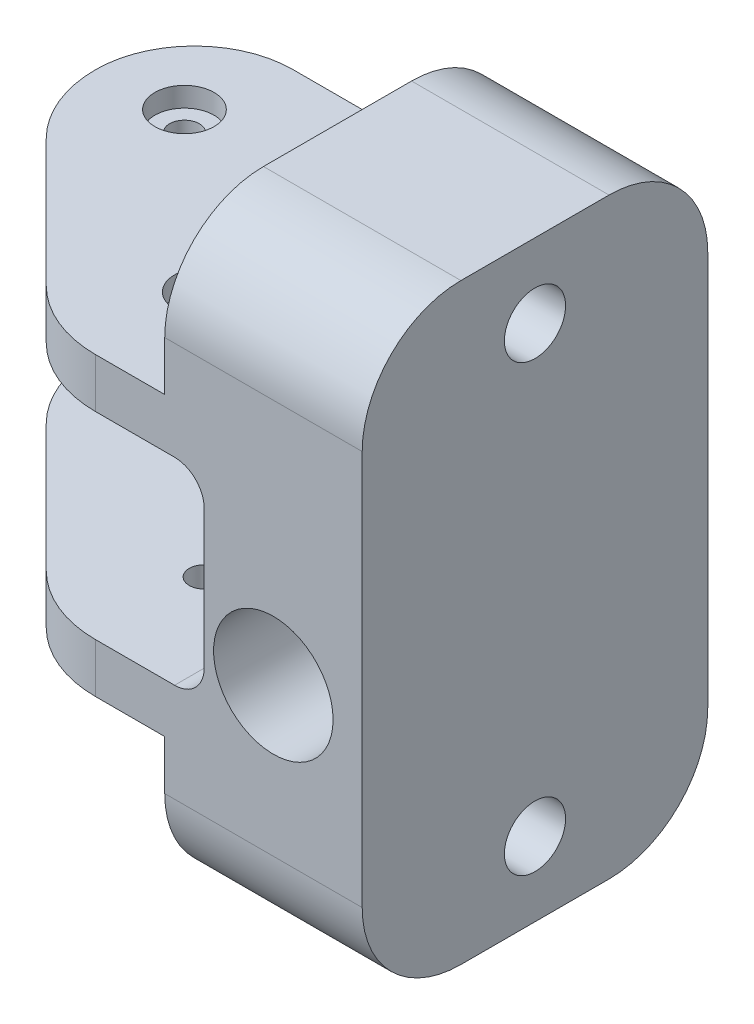
SolidWorks part; units mm, degrees
ref_plane "前视基准面" through (0, 0, 0) normal (0, 0, 1) x (1, 0, 0)
ref_plane "上视基准面" through (0, 0, 0) normal (0, 1, 0) x (1, 0, 0)
ref_plane "右视基准面" through (0, 0, 0) normal (1, 0, 0) x (0, 0, -1)
other "Configuration Table"
sketch "草图1" plane through (0, 0, 0) normal (0, 1, 0) x (1, 0, 0)
  line L0 (-25, -17.5) -> (5, -17.5)
  line L1 (25, 17.5) -> (25, 2.5)
  line L2 (25, 2.5) -> (5, -17.5)
  line L7 (-25, -17.5) -> (-25, 17.5)
  line L8 (-25, 17.5) -> (25, 17.5)
extrude "凸台-拉伸1" add sketch "草图1" along normal blind 60 contours L2 L0 L7 L8 L1
sketch "草图2" plane through (0, 0, -17.5) normal (0, 0, -1) x (-1, 0, 0)
  line L0 (25, 0) -> (7, 0)
  line L1 (25, 0) -> (-25, 0) construction
  line L2 (7, 0) -> (7, 60)
  line L3 (25, 60) -> (-25, 60) construction
  line L5 (-25, 60) -> (7, 60)
  line L6 (-25, 60) -> (-25, 45)
  line L7 (-25, 45) -> (7, 45)
  line L8 (7, 60) -> (7, 45)
  line L9 (-25, 0) -> (7, 0)
  line L10 (-25, 0) -> (-25, 15)
  line L11 (-25, 15) -> (7, 15)
  line L12 (7, 0) -> (7, 15)
  line M11 (-25, 0) -> (25, 0)
  line M13 (25, 60) -> (-25, 60)
  line M14 (-25, 60) -> (-25, 0)
extrude "切除-拉伸1" cut sketch "草图2" against normal blind 60 contours L7 L2 M14 M13 | L11 L2 M14 M11
sketch "草图3" plane through (-25, 0, 0) normal (-1, 0, 0) x (0, 0, 1)
  line L0 (-17.5, 60) -> (17.5, 0)
  line L1 (0, 30) -> (0, 52.5)
  line L2 (0, 30) -> (0, 7.5)
  circle A0 centre (0, 52.5) radius 3
  circle A1 centre (0, 7.5) radius 3
extrude "切除-拉伸2" cut sketch "草图3" against normal blind 30
sketch "草图4" plane through (-25, 0, 0) normal (-1, 0, 0) x (0, 0, 1)
  line L1 (-17.5, 60) -> (-7.5, 60)
  line L2 (-17.5, 60) -> (-17.5, 50)
  line L5 (17.5, 60) -> (7.5, 60)
  line L6 (17.5, 60) -> (17.5, 50)
  line L9 (-17.5, 0) -> (-7.5, 0)
  line L10 (-17.5, 0) -> (-17.5, 10)
  line L13 (17.5, 0) -> (7.5, 0)
  line L14 (17.5, 0) -> (17.5, 10)
  arc A0 (-17.5, 50) -> (-7.5, 60) centre (-7.5, 50) cw
  arc A1 (17.5, 50) -> (7.5, 60) centre (7.5, 50) ccw
  arc A2 (-17.5, 10) -> (-7.5, 0) centre (-7.5, 10) ccw
  arc A3 (17.5, 10) -> (7.5, 0) centre (7.5, 10) cw
  line M20 (-17.5, 0) -> (17.5, 0)
  line M21 (17.5, 0) -> (17.5, 60)
  line M22 (17.5, 60) -> (-17.5, 60)
  line M23 (-17.5, 60) -> (-17.5, 0)
extrude "切除-拉伸3" cut sketch "草图4" against normal blind 30 contours A0 M23 M22 | A1 M21 M22 | A3 M21 M20 | A2 M23 M20
sketch "草图5" plane through (0, 0, -17.5) normal (0, 0, -1) x (-1, 0, 0)
  line L0 (5, 37) -> (5, 23)
  line L2 (11, 37) -> (11, 23)
  arc A0 (11, 23) -> (5, 23) centre (8, 23) cw
  arc A1 (5, 37) -> (11, 37) centre (8, 37) cw
extrude "切除-拉伸4" cut sketch "草图5" against normal blind 50
sketch "草图6" plane through (0, 0, -17.5) normal (0, 0, -1) x (-1, 0, 0)
  circle A1 centre (18, 25) radius 5
extrude "切除-拉伸5" cut sketch "草图6" against normal blind 50
sketch "草图7" plane through (0, 0, -17.5) normal (0, 0, -1) x (-1, 0, 0)
  line L0 (-8, 40) -> (-25, 40)
  line L1 (-25, 45) -> (-25, 15) construction
  line L2 (-5, 23) -> (-5, 30)
  line L3 (5, 30) -> (-5, 30)
  line L4 (5, 37) -> (5, 23) construction
  line L5 (-5, 37) -> (-5, 30)
  line L6 (-8, 20) -> (-25, 20)
  line L7 (-25, 20) -> (-25, 40)
  arc A2 (-5, 37) -> (-8, 40) centre (-8, 37) ccw
  arc A3 (-8, 20) -> (-5, 23) centre (-8, 23) ccw
  line M26 (-25, 45) -> (-25, 15)
extrude "切除-拉伸6" cut sketch "草图7" against normal blind 50 contours L6 A3 L2 L5 A2 L0 M26
sketch "草图8" plane through (5, 0, 0) normal (1, 0, 0) x (0, 0, -1)
  line L0 (17.5, 37) -> (3.5, 37)
  line L1 (-17.5, 37) -> (17.5, 37) construction
  line L2 (3.5, 37) -> (3.5, 40)
  line L3 (-14.5, 40) -> (17.5, 40) construction
  line L5 (3.5, 40) -> (-17.5, 40)
  line L6 (3.5, 40) -> (3.5, 20)
  line L7 (3.5, 20) -> (-17.5, 20)
  line L8 (-17.5, 40) -> (-17.5, 20)
  line M6 (-17.5, 37) -> (-17.5, 23)
  line M7 (-17.5, 23) -> (17.5, 23)
  line M9 (17.5, 37) -> (-17.5, 37)
extrude "切除-拉伸7" cut sketch "草图8" against normal blind 13 contours L6 M9 M6 M7 | L5 L8 L2 M9 | L8 L7 L6 M7
sketch "草图9" plane through (5, 0, 0) normal (-1, 0, 0) x (0, 0, 1)
  line L1 (-3.5, 40) -> (17.5, 40)
  line L2 (-3.5, 40) -> (-3.5, 37)
  line L3 (-3.5, 37) -> (17.5, 37)
  line L4 (17.5, 40) -> (17.5, 37)
  line L5 (-3.5, 20) -> (17.5, 20)
  line L6 (-3.5, 20) -> (-3.5, 23)
  line L7 (-3.5, 23) -> (17.5, 23)
  line L8 (17.5, 20) -> (17.5, 23)
extrude "切除-拉伸8" cut sketch "草图9" against normal blind 13
sketch "草图10" plane through (0, 15, 0) normal (0, -1, 0) x (-1, 0, 0)
  line L0 (-25, 2.5) -> (-21.4645, -1.0355)
  line L1 (-5, -17.5) -> (-25, 2.5) construction
  line L2 (-25, 2.5) -> (-25, 7.5)
  line L3 (-25, 2.5) -> (-25, 17.5) construction
  line L9 (-25, 17.5) -> (-15, 17.5)
  line L10 (-25, 17.5) -> (-25, 7.5)
  arc A0 (-21.4645, -1.0355) -> (-25, 7.5) centre (-12.9289, 7.5) cw
  arc A2 (-15, 17.5) -> (-25, 7.5) centre (-15, 7.5) ccw
  line M10 (7, 17.5) -> (-25, 17.5)
  line M11 (-25, 17.5) -> (-25, 2.5)
extrude "切除-拉伸10" cut sketch "草图10" against normal blind 50 contours A2 M10 M11 | L2 L0 A0
sketch "草图11" plane through (0, 45, 0) normal (0, 1, 0) x (1, 0, 0)
  line L0 (5, -17.5) -> (8.5355, -13.9645)
  line L1 (5, -17.5) -> (21.4645, -1.0355) construction
  line L2 (5, -17.5) -> (0, -17.5)
  line L3 (5, -17.5) -> (-7, -17.5) construction
  arc A0 (0, -17.5) -> (8.5355, -13.9645) centre (0, -5.4289) ccw
extrude "切除-拉伸11" cut sketch "草图11" against normal blind 50 contours A0 L0 L2
sketch "草图15" plane through (0, 20, 0) normal (0, 1, 0) x (1, 0, 0)
  line L0 (8, 17.5) -> (8, 8.5)
  line L2 (8, 3.5) -> (8, 17.5) construction
  line L3 (8, 8.5) -> (17, 8.5)
  circle A0 centre (17, 8.5) radius 1.51
extrude "切除-拉伸14" cut sketch "草图15" against normal blind 100
sketch "草图16" plane through (0, 15, 0) normal (0, -1, 0) x (1, 0, 0)
  circle A0 centre (17, -8.5) radius 1.51
extrude "切除-拉伸15" cut sketch "草图16" against normal blind 100 contours A0
sketch "草图17" plane through (0, 40, 0) normal (0, -1, 0) x (-1, 0, 0)
  line L0 (-8, 3.5) -> (8, 3.5)
  line L2 (0, 3.5) -> (0, -6.5)
  circle A1 centre (0, -6.5) radius 1.51
extrude "切除-拉伸16" cut sketch "草图17" against normal blind 100
sketch "草图18" plane through (0, 45, 0) normal (0, 1, 0) x (1, 0, 0)
  circle A0 centre (0, -6.5) radius 1.51
extrude "切除-拉伸17" cut sketch "草图18" against normal blind 100
sketch "草图21" plane through (0, 45, 0) normal (0, 1, 0) x (1, 0, 0)
  circle A0 centre (0, -6.5) radius 3
  circle A1 centre (17, 8.5) radius 3
extrude "切除-拉伸18" cut sketch "草图21" against normal blind 2 contours A1 | A0
sketch "草图22" plane through (0, 15, 0) normal (0, -1, 0) x (-1, 0, 0)
  circle A0 centre (0, -6.5) radius 3
  circle A1 centre (-17, 8.5) radius 3
extrude "切除-拉伸19" cut sketch "草图22" against normal blind 2 contours A0 | A1
sketch "草图23" plane through (0, 0, -17.5) normal (0, 0, -1) x (-1, 0, 0)
  circle A0 centre (18, 25) radius 5.05
extrude "切除-拉伸20" cut sketch "草图23" against normal blind 100
sketch "草图24" plane through (-25, 0, 0) normal (-1, 0, 0) x (0, 0, 1)
  circle A0 centre (0, 52.5) radius 3.05
  circle A1 centre (0, 7.5) radius 3.05
extrude "切除-拉伸21" cut sketch "草图24" against normal blind 100 contours A0
sketch "草图25" plane through (-25, 0, 0) normal (-1, 0, 0) x (0, 0, 1)
  circle A1 centre (0, 7.5) radius 3.05
extrude "切除-拉伸22" cut sketch "草图25" against normal blind 30 contours A1
sketch "草图27" plane through (0, 0, -17.5) normal (0, 0, -1) x (-1, 0, 0)
  circle A0 centre (18, 25) radius 6.05
extrude "切除-拉伸23" cut sketch "草图27" against normal blind 50
mirror "镜向4" about plane through (-25, 60, 17.5) normal (-1, 0, 0) of "切除-拉伸14", "切除-拉伸17", "切除-拉伸15", "切除-拉伸16", "凸台-拉伸1", "切除-拉伸1", "切除-拉伸4", "切除-拉伸6", "切除-拉伸7", "切除-拉伸10", "切除-拉伸11", "切除-拉伸18", "切除-拉伸19"
sketch "草图28" plane through (-7, 0, 0) normal (1, 0, 0) x (0, 0, -1)
  line L4 (-17.5, 0) -> (-17.5, 10)
  line L9 (17.5, 10) -> (17.5, 0) construction
  line L10 (-17.5, 0) -> (-7.5, 0)
  line L11 (7.5, 0) -> (17.5, 0)
  line L12 (17.5, 0) -> (17.5, 10)
  arc A0 (-7.5, 0) -> (-17.5, 10) centre (-7.5, 10) cw
  arc A1 (-17.5, 10) -> (-7.5, 0) centre (-7.5, 10) ccw construction
  arc A2 (7.5, 0) -> (17.5, 10) centre (7.5, 10) ccw
  circle A3 centre (0, 7.5) radius 3.05
extrude "切除-拉伸24" cut sketch "草图28" against normal blind 100 contours L10 A0 L4 | A3 | L12 A2 L11
sketch "草图29" plane through (-7, 0, 0) normal (1, 0, 0) x (0, 0, -1)
  line L0 (-17.5, 50) -> (-17.5, 60)
  line L1 (-17.5, 60) -> (-7.5, 60)
  line L2 (17.5, 60) -> (7.5, 60)
  line L3 (17.5, 60) -> (17.5, 50)
  arc A0 (17.5, 50) -> (7.5, 60) centre (7.5, 50) ccw construction
  arc A1 (17.5, 50) -> (7.5, 60) centre (7.5, 50) ccw construction
  circle A2 centre (0, 52.5) radius 3.05
  arc A3 (-17.5, 50) -> (-7.5, 60) centre (-7.5, 50) cw
  arc A4 (17.5, 50) -> (7.5, 60) centre (7.5, 50) ccw
  circle M2 centre (0, 52.5) radius 3.05
  arc M7 (17.5, 50) -> (7.5, 60) centre (7.5, 50) ccw
extrude "切除-拉伸25" cut sketch "草图29" against normal blind 100 contours M2 | L3 L2 M7 | L0 L1 A3
sketch "草图30" plane through (0, 0, 17.5) normal (0, 0, 1) x (1, 0, 0)
  circle A1 centre (-32, 25) radius 6.05
extrude "切除-拉伸26" cut sketch "草图30" against normal blind 100 contours A1
sketch "草图31" plane through (0, 0, 17.5) normal (0, 0, 1) x (1, 0, 0)
  line L0 (-7, 60) -> (-43, 60) construction
  line L1 (-25, 60) -> (35.7996, 60)
  line L2 (-25, 60) -> (-25, -6.6248)
  line L3 (-25, -6.6248) -> (35.7996, -6.6248)
  line L4 (35.7996, 60) -> (35.7996, -6.6248)
extrude "切除-拉伸27" cut sketch "草图31" against normal blind 100
sketch "草图32" plane through (-55, 0, 0) normal (1, 0, 0) x (0, 0, -1)
  line L1 (3.5, 40) -> (-16.4158, 40)
  line L2 (3.5, 40) -> (3.5, 37)
  line L3 (3.5, 37) -> (-16.4158, 37)
  line L4 (-16.4158, 40) -> (-16.4158, 37)
  line L5 (3.5, 20) -> (-16.4158, 20)
  line L6 (3.5, 20) -> (3.5, 23)
  line L7 (3.5, 23) -> (-16.4158, 23)
  line L8 (-16.4158, 20) -> (-16.4158, 23)
extrude "切除-拉伸28" cut sketch "草图32" against normal blind 100
sketch "草图33" plane through (-25, 0, 0) normal (1, 0, 0) x (0, 0, -1)
  line L2 (-7.5, 60) -> (7.5, 60)
  line L5 (17.5, 50) -> (17.5, 10)
  line L6 (17.5, 10) -> (17.5, 50) construction
  line L9 (7.5, 0) -> (-7.5, 0)
  line L12 (-17.5, 10) -> (-17.5, 50)
  arc A0 (7.5, 0) -> (17.5, 10) centre (7.5, 10) ccw construction
  arc A1 (-17.5, 50) -> (-7.5, 60) centre (-7.5, 50) cw
  arc A2 (17.5, 50) -> (7.5, 60) centre (7.5, 50) ccw
  arc A3 (-17.5, 10) -> (-7.5, 0) centre (-7.5, 10) ccw
  arc A4 (17.5, 10) -> (7.5, 0) centre (7.5, 10) cw
  circle A5 centre (0, 7.5) radius 3.05
  circle A6 centre (0, 52.5) radius 3.05
extrude "凸台-拉伸2" add sketch "草图33" along normal blind 2
sketch "草图34" plane through (-23, 0, 0) normal (1, 0, 0) x (0, 0, -1)
  circle A0 centre (0, 52.5) radius 3.1
  circle A1 centre (0, 7.5) radius 3.1
extrude "切除-拉伸29" cut sketch "草图34" against normal blind 30 contours A1 | A0
